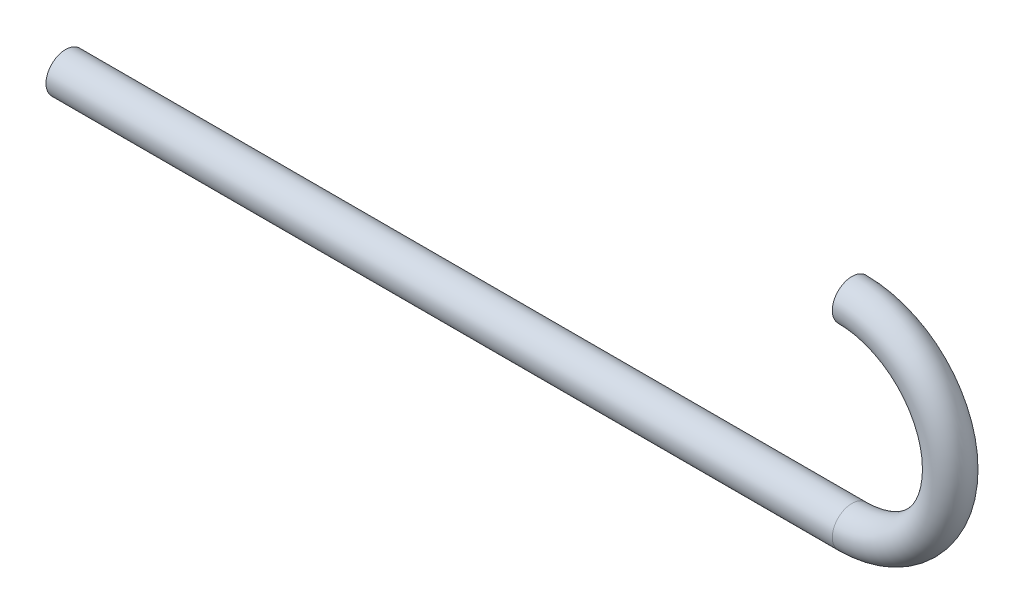
SolidWorks part; units mm, degrees
material "不锈钢"
ref_plane "前基準面" through (0, 0, 0) normal (0, 0, 1) x (1, 0, 0)
ref_plane "cf" through (0, 0, 0) normal (0, 1, 0) x (1, 0, 0)
ref_plane "右基準面" through (0, 0, 0) normal (1, 0, 0) x (0, 0, -1)
sketch "草图1" plane through (0, 0, 0) normal (0, 0, 1) x (1, 0, 0)
  line L0 (0, 0) -> (120, 0)
  arc A0 (120, 0) -> (120, 30) centre (120, 15) ccw
  dimension "D1" = 15
  dimension "D2" = 120
sketch "草图3" plane through (0, 0, 0) normal (1, 0, 0) x (0, 0, -1)
  circle A0 centre (0, 0) radius 3
  dimension "D1" = 6
sweep "扫描1" add profiles "草图3" path "草图1"
cosmetic thread "装饰螺纹线1"
